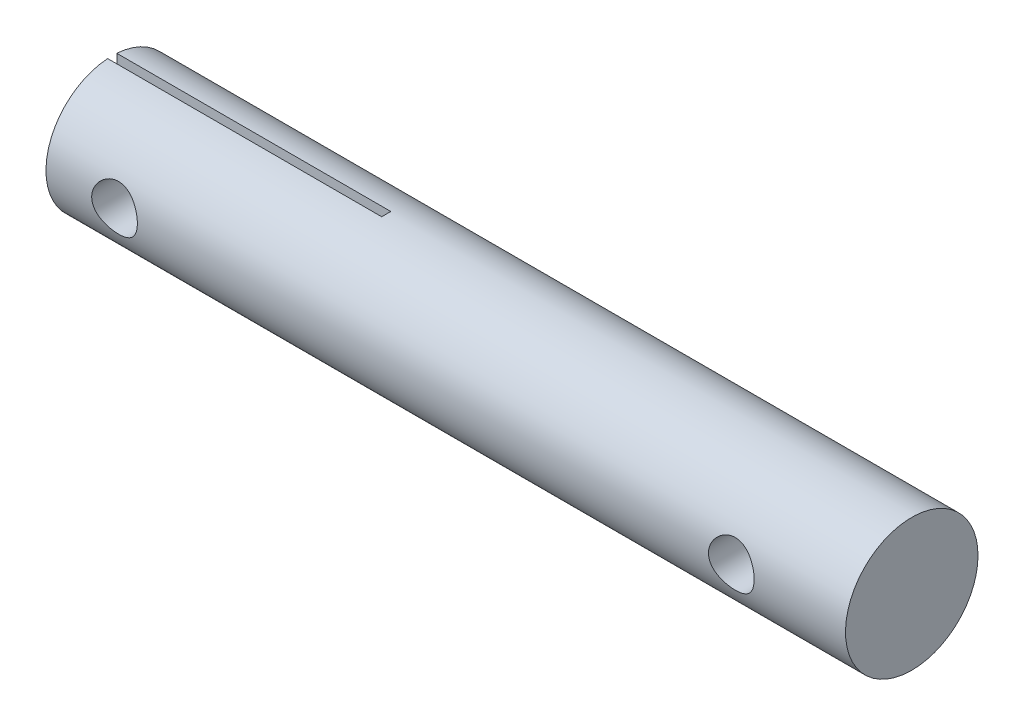
SolidWorks part; units mm, degrees
ref_plane "前视基准面" through (0, 0, 0) normal (0, 0, 1) x (1, 0, 0)
ref_plane "上视基准面" through (0, 0, 0) normal (0, 1, 0) x (1, 0, 0)
ref_plane "右视基准面" through (0, 0, 0) normal (1, 0, 0) x (0, 0, -1)
other "Configuration Table"
sketch "草图1" plane through (0, 0, 0) normal (1, 0, 0) x (0, 0, -1)
  circle A0 centre (0, 0) radius 2.9
  dimension "D1" = 5.8
extrude "凸台-拉伸1" add sketch "草图1" along normal blind 35
sketch "草图2" plane through (0, 0, 0) normal (-1, 0, 0) x (0, 0, 1)
  line L0 (0, 2.9) -> (0, -2.9) construction
  line L2 (-0.2, 3.1215) -> (0.2, 3.1215)
  line L3 (-0.2, 3.1215) -> (-0.2, -2.329)
  line L4 (-0.2, -2.329) -> (0.2, -2.329)
  line L5 (0.2, 3.1215) -> (0.2, -2.329)
  circle A0 centre (0, 0) radius 2.9 construction
  dimension "D1" = 0.4
  dimension "D2" = 0.2
extrude "切除-拉伸1" cut sketch "草图2" against normal blind 12
sketch "草图3" plane through (0, 0, 0.2) normal (0, 0, -1) x (-1, 0, 0)
  line L0 (0, -0.0035) -> (-6.0327, -0.0035) construction
  line L1 (0, -2.9) -> (0, 2.8931) construction
  line L2 (-35, 2.9) -> (-35, -2.9) construction
  circle A0 centre (-3, -0.0035) radius 1
  circle A1 centre (-30, -0.0035) radius 1
  dimension "D1" = 2
  dimension "D4" = 2
  dimension "D2" = 3
  dimension "D3" = 5
extrude "切除-拉伸2" cut sketch "草图3" against normal blind 10 and the other way blind 10
